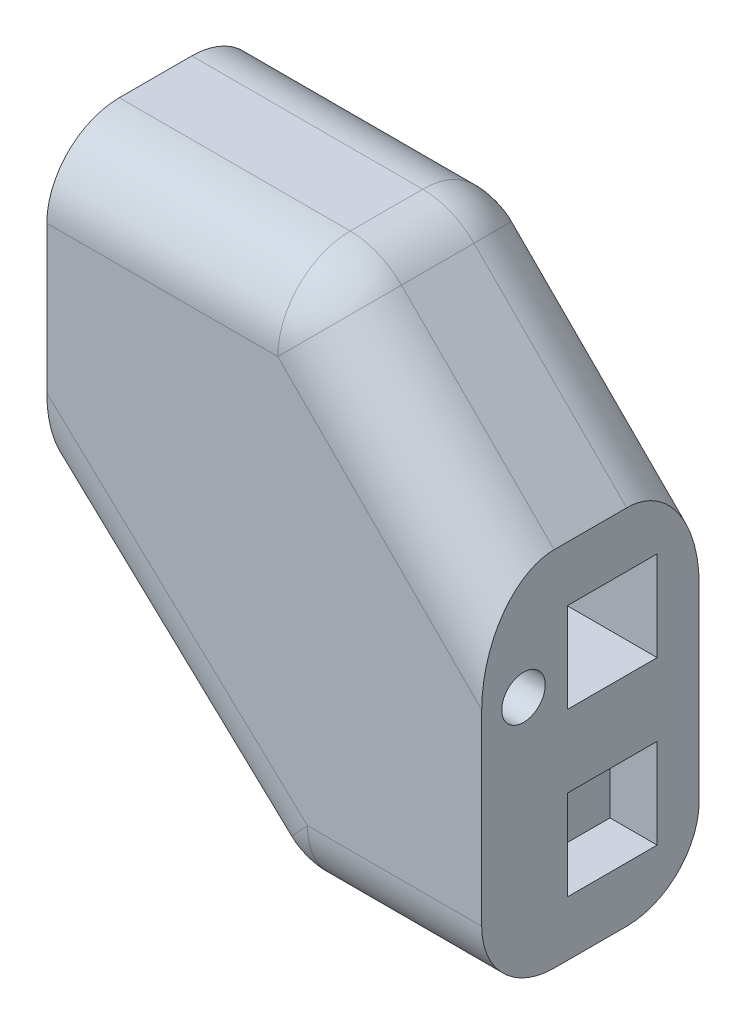
SolidWorks part; units mm, degrees
ref_plane "Front Plane" through (0, 0, 0) normal (0, 0, 1) x (1, 0, 0)
ref_plane "Top Plane" through (0, 0, 0) normal (0, 1, 0) x (1, 0, 0)
ref_plane "Right Plane" through (0, 0, 0) normal (1, 0, 0) x (0, 0, -1)
sketch "Sketch2" plane through (0, 0, 0) normal (0, 0, 1) x (1, 0, 0)
  line L2 (29.5, -24.5) -> (29.5, 0.5)
  line L3 (29.5, 0.5) -> (17.5, 12.5)
  line L4 (17.5, 12.5) -> (-0.5, 12.5)
  line L5 (-0.5, 12.5) -> (-0.5, -9.5)
  line L6 (-0.5, -9.5) -> (15.5, -24.5)
  line L7 (15.5, -24.5) -> (29.5, -24.5)
  dimension "D1" = 25
  dimension "D2" = 14
  dimension "D3" = 135
  dimension "D4" = 12
  dimension "D5" = 15
  dimension "D6" = 18
extrude "Boss-Extrude1" add sketch "Sketch2" along normal blind 15
fillet "Fillet1" radius 5 10 edges at (15.5, -24.5, 7.5) (22.5, -24.5, 0) (7.5, -17, 0) (22.5, -24.5, 15) (7.5, -17, 15) (17.5, 12.5, 7.5) (23.5, 6.5, 0) (23.5, 6.5, 15) (8.5, 12.5, 0) (8.5, 12.5, 15)
sketch "Sketch4" plane through (29.5, 0, 0) normal (1, 0, 0) x (0, 0, -1)
  line L0 (-10, 0.5) -> (-5, 0.5) construction
  line L1 (-5, 0.5) -> (-5, -24.5) construction
  line L2 (-5, -24.5) -> (-10, -24.5) construction
  line L3 (-10, -24.5) -> (-10, 0.5) construction
  line L4 (-10, -12) -> (-5, -12) construction
  line L5 (-9.1, -20.7) -> (-9.1, -14.5)
  line L6 (-9.1, -3.3) -> (-2.9, -3.3)
  line L7 (-9.1, -3.3) -> (-9.1, -9.5)
  line L8 (-9.1, -9.5) -> (-2.9, -9.5)
  line L9 (-2.9, -3.3) -> (-2.9, -9.5)
  line L10 (-9.1, -3.3) -> (-2.9, -9.5) construction
  line L11 (-9.1, -9.5) -> (-2.9, -3.3) construction
  line L12 (-9.1, -14.5) -> (-2.9, -14.5)
  line L13 (-2.9, -20.7) -> (-2.9, -14.5)
  line L14 (-9.1, -20.7) -> (-2.9, -20.7)
  point P10 (-6, -6.4)
  dimension "D1" = 6.2
  dimension "D2" = 6.2
  dimension "D3" = 2.5
extrude "Cut-Extrude1" cut sketch "Sketch4" against normal blind 3.25
sketch "Sketch5" plane through (-0.5, 0, 0) normal (-1, 0, 0) x (0, 0, 1)
  line L0 (5, -9.5) -> (5, 12.5) construction
  line L1 (5, 12.5) -> (10, 12.5) construction
  line L2 (10, 12.5) -> (10, -9.5) construction
  line L3 (10, 1.5) -> (5, 1.5) construction
  line L5 (4.4, 4.6) -> (10.6, 4.6)
  line L6 (4.4, 4.6) -> (4.4, -1.6)
  line L7 (4.4, -1.6) -> (10.6, -1.6)
  line L8 (10.6, 4.6) -> (10.6, -1.6)
  line L9 (4.4, 4.6) -> (10.6, -1.6) construction
  line L10 (4.4, -1.6) -> (10.6, 4.6) construction
  point P10 (7.5, 1.5)
  dimension "D1" = 6.2
  dimension "D2" = 6.2
extrude "Cut-Extrude2" cut sketch "Sketch5" against normal blind 3.25
sketch "Sketch8" plane through (2.75, 0, 0) normal (-1, 0, 0) x (0, 0, 1)
  line L1 (4.4, 4.6) -> (10.6, 4.6)
  line L2 (4.4, 4.6) -> (4.4, -1.6)
  line L3 (4.4, -1.6) -> (10.6, -1.6)
  line L4 (10.6, 4.6) -> (10.6, -1.6)
  dimension "D1" = 6.2
  dimension "D2" = 6.2
extrude "Cut-Extrude3" cut sketch "Sketch8" against normal blind 10
sketch "Sketch9" plane through (0, -1.6, 0) normal (0, 1, 0) x (1, 0, 0)
  line L1 (12.7684, -4.3996) -> (12.7268, -4.3996)
  line L2 (12.7684, -4.3996) -> (12.7684, -4.4412)
  line L3 (12.7684, -4.4412) -> (12.7268, -4.4412)
  line L4 (12.7268, -4.3996) -> (12.7268, -4.4412)
  line L5 (12.7268, -4.4412) -> (6.5268, -4.4412)
  line L6 (12.7268, -4.4412) -> (12.7268, -10.6412)
  line L7 (12.7268, -10.6412) -> (6.5268, -10.6412)
  line L8 (6.5268, -4.4412) -> (6.5268, -10.6412)
  line M4 (-0.5, -10.6) -> (12.75, -10.6)
  dimension "D1" = 6.2
  dimension "D2" = 6.2
extrude "Cut-Extrude4" cut sketch "Sketch9" against normal blind 8 contours L5 L8 L6 M4
sketch "Sketch10" plane through (26.25, 0, 0) normal (1, 0, 0) x (0, 0, -1)
  line L1 (-2.9, -9.5) -> (-9.1, -9.5)
  line L2 (-2.9, -9.5) -> (-2.9, -3.2553)
  line L3 (-2.9, -3.2553) -> (-9.1, -3.2553)
  line L4 (-9.1, -9.5) -> (-9.1, -3.2553)
  dimension "D1" = 6.2
extrude "Cut-Extrude6" cut sketch "Sketch10" against normal blind 20
sketch "Sketch11" plane through (29.5, 0, 0) normal (1, 0, 0) x (0, 0, -1)
  line L0 (-12.1185, -12) -> (-12.1185, -7.2638) construction
  line L1 (-6, -9.5) -> (-6, -14.5) construction
  line L2 (-9.1, -9.5) -> (-2.9, -9.5) construction
  line L3 (-2.9, -14.5) -> (-9.1, -14.5) construction
  line L4 (-6, -14.5) -> (-6, -12) construction
  line L5 (-6, -12) -> (-15, -12) construction
  line L6 (-15, -19.5) -> (-15, -6.5711) construction
  circle A1 centre (-12.1185, -7.2638) radius 1.5
  dimension "D1" = 3
extrude "Cut-Extrude7" cut sketch "Sketch11" against normal blind 36
